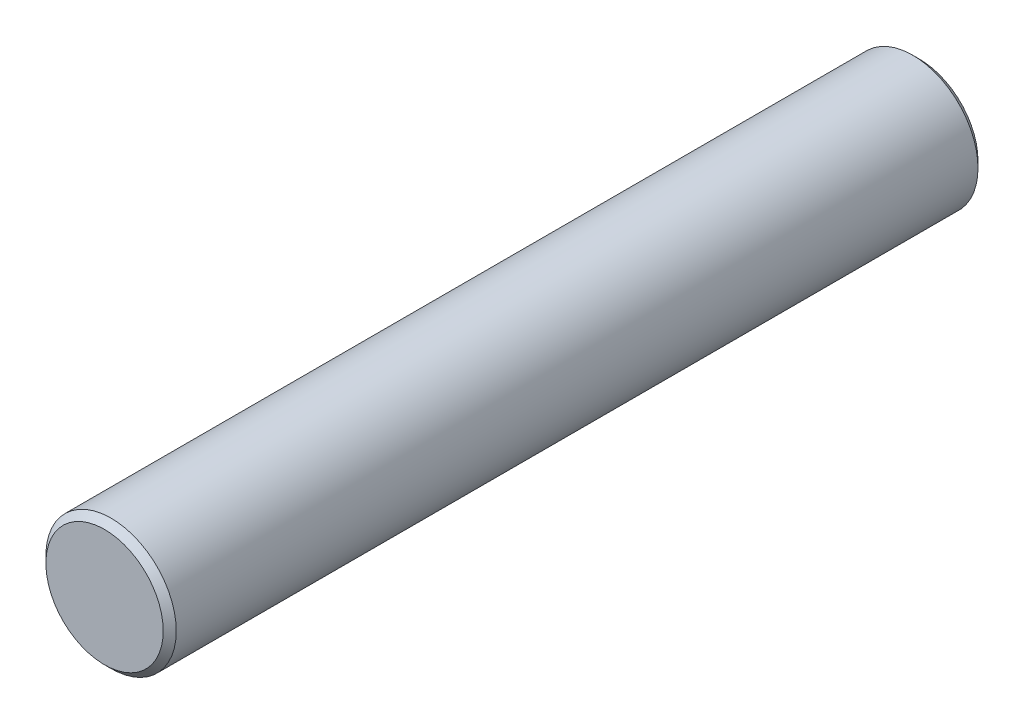
SolidWorks part; units mm, degrees
ref_plane "Спереди" through (0, 0, 0) normal (0, 0, 1) x (1, 0, 0)
ref_plane "Сверху" through (0, 0, 0) normal (0, 1, 0) x (1, 0, 0)
ref_plane "Справа" through (0, 0, 0) normal (1, 0, 0) x (0, 0, -1)
sketch "Эскиз1" plane through (0, 0, 0) normal (0, 0, 1) x (1, 0, 0)
  circle A0 centre (0, 0) radius 10
extrude "Бобышка-Вытянуть1" add sketch "Эскиз1" along normal blind 125
chamfer "Фаска1" distance 1 angle 45 2 edges at (10, 0, 125) (10, 0, 0)
